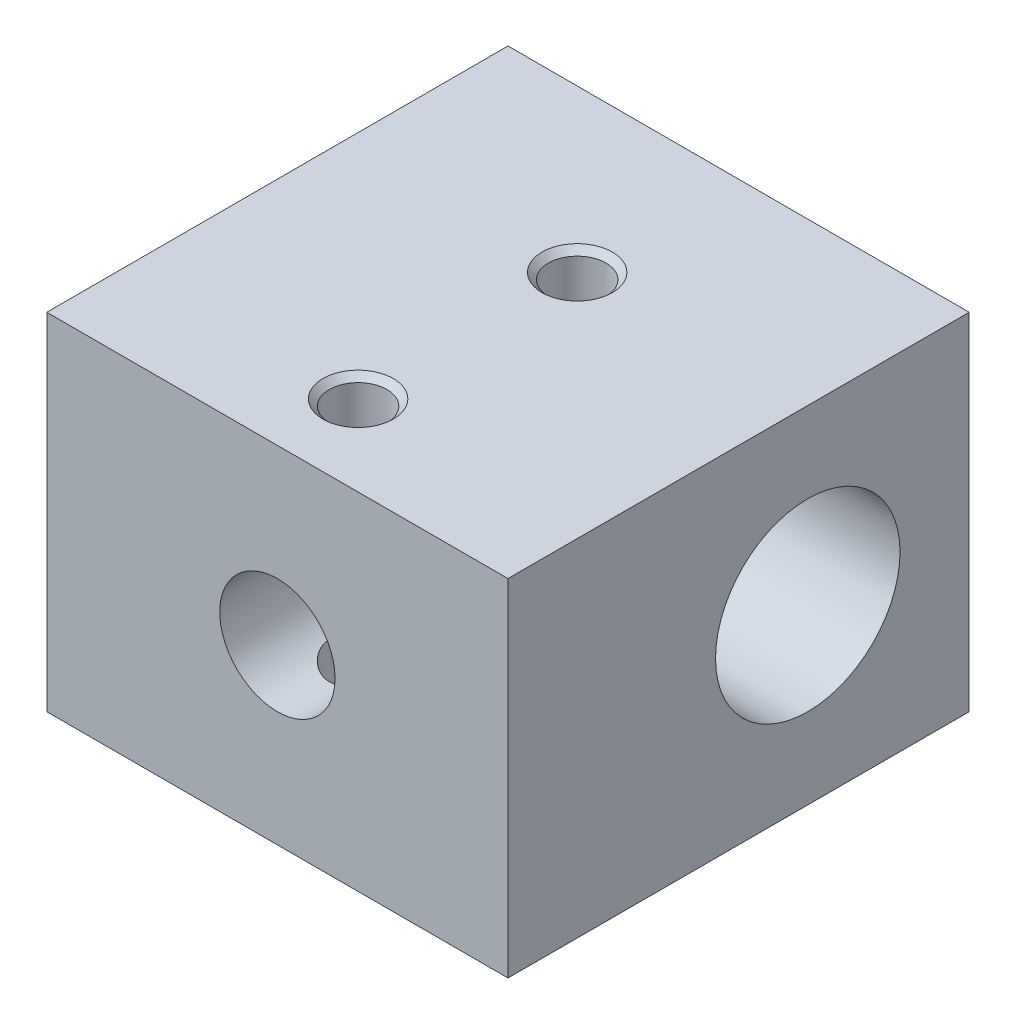
SolidWorks part; units mm, degrees
material "1.0037 (S235JR)"
ref_plane "Ebene vorne" through (0, 0, 0) normal (0, 0, 1) x (1, 0, 0)
ref_plane "Ebene oben" through (0, 0, 0) normal (0, 1, 0) x (1, 0, 0)
ref_plane "Ebene rechts" through (0, 0, 0) normal (1, 0, 0) x (0, 0, -1)
sketch "Skizze1" plane through (0, 0, 0) normal (0, 1, 0) x (1, 0, 0)
  line L1 (0, 0) -> (20, 0)
  line L2 (0, 0) -> (0, 20)
  line L3 (0, 20) -> (20, 20)
  line L4 (20, 0) -> (20, 20)
  dimension "D1" = 20
  dimension "D2" = 20
extrude "Aufsatz-Linear austragen1" add sketch "Skizze1" along normal blind 15
sketch "Skizze2" plane through (0, 0, 0) normal (0, 0, 1) x (1, 0, 0)
  line L0 (0, 15) -> (20, 0) construction
  circle A0 centre (10, 7.5) radius 2.5
  dimension "D1" = 5
extrude "Schnitt-Linear austragen1" cut sketch "Skizze2" against normal blind 7
sketch "Skizze4" plane through (20, 0, 0) normal (1, 0, 0) x (0, 0, -1)
  line L0 (20, 7.5) -> (0, 7.5) construction
  line L1 (20, 15) -> (20, 0) construction
  line L2 (0, 15) -> (0, 0) construction
  circle A0 centre (13, 7.5) radius 4
  dimension "D1" = 8
  dimension "D2" = 7
extrude "Schnitt-Linear austragen7" cut sketch "Skizze4" against normal through all
ref_plane "Ebene1" through (10, 0, 0) normal (1, 0, 0) x (0, 0, -1)
hole_wizard "M3x0.5 Gewindebohrung1" positions "Skizze5" profile "Skizze6" tap size "M3x0.5" standard "ANSI Metrisch" end condition through all
sketch "Skizze5" plane through (12, 15, 0) normal (0, -1, 0) x (0, 0, 1)
  line L1 (0, 2) -> (-3.5, 2) construction
  line L3 (0, 12) -> (0, -8) construction
  line L5 (-20, -8) -> (-20, 12) construction
  line L6 (-3.5, 2) -> (-13, 2) construction
  point P0 (-3.5, 2)
  point P18 (-13, 2)
  dimension "D1" = 3.5
  dimension "D2" = 7
sketch "Skizze6" plane through (10, 15, -3.5) normal (1, 0, 0) x (0, 0, 1)
  line L0 (0, 0) -> (0, 15)
  line L1 (0, 15) -> (1.25, 15)
  line L2 (1.25, 15) -> (1.25, 0.275)
  line L3 (1.25, 0.275) -> (1.525, 0)
  line L5 (1.525, 0) -> (0, 0)
  line L6 (-1.25, 0.275) -> (-1.525, 0) construction
  line L11 (0, -6.35) -> (0, 107.95) construction
  dimension "Bohrerdurchmesser" = 2.5
  dimension "Bohrungstiefe" = 15
  dimension "Senkdurchmesser (Oben)" = 3.05
  dimension "Senkwinkel (Oben)" = 90
cosmetic thread "Bohrungsgewinde1" parameters "D2"=3
cosmetic thread "Bohrungsgewinde2" parameters "D2"=3
